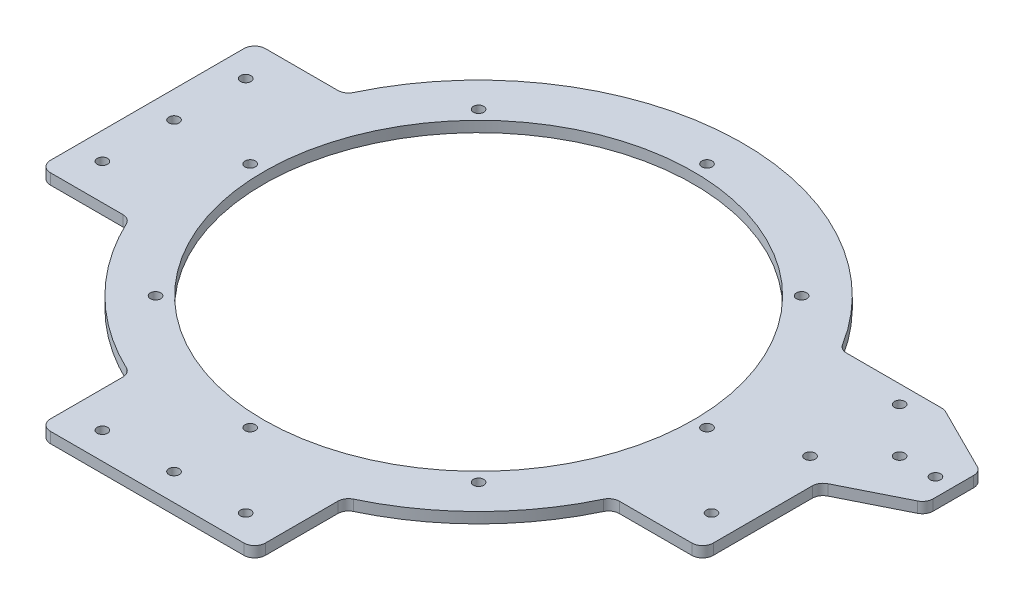
SolidWorks part; units mm, degrees
material "Thornel Mat VMA"
ref_plane "前视基准面" through (0, 0, 0) normal (0, 0, 1) x (1, 0, 0)
ref_plane "上视基准面" through (0, 0, 0) normal (0, 1, 0) x (1, 0, 0)
ref_plane "右视基准面" through (0, 0, 0) normal (1, 0, 0) x (0, 0, -1)
other "Configuration Table"
sketch "草图1" plane through (0, 0, 0) normal (0, 1, 0) x (1, 0, 0)
  line L0 (-94.2968, 0) -> (104.7583, 0) construction
  line L1 (0, 85) -> (0, -117.5844) construction
  line L2 (-45.0781, 45.0781) -> (0, 0) construction
  line L3 (-41.1681, -85) -> (39.8954, -85) construction
  line L4 (-42.9076, 77.5) -> (64.6874, 77.5) construction
  line L5 (-85, 28.1793) -> (-85, -30) construction
  line L6 (85, 63.75) -> (85, -19.3516) construction
  line L12 (-30, -92.5) -> (30, -92.5)
  line L15 (92.5, -30) -> (92.5, 30) construction
  line L18 (30, 85) -> (-30, 85) construction
  line L19 (-92.5, 30) -> (-92.5, -30)
  line L20 (-30, -92.5) -> (-30, -67.3726)
  line L21 (30, -92.5) -> (30, -67.3726)
  line L22 (-92.5, -30) -> (-67.3726, -30)
  line L23 (-92.5, 30) -> (-67.3726, 30)
  line L24 (92.5, 30) -> (67.3726, 30) construction
  line L25 (92.5, -30) -> (67.3726, -30)
  line L26 (-30, 85) -> (-30, 67.3726) construction
  line L27 (30, 85) -> (30, 67.3726) construction
  line L28 (65.6866, 20) -> (127.8038, 20) construction
  line L29 (92.5, 30) -> (92.5, 37.5) construction
  line L30 (92.5, 37.5) -> (63.5044, 37.5)
  line L31 (92.5, 37.5) -> (112.5, 27.5)
  line L32 (112.5, 27.5) -> (112.5, 12.5)
  line L33 (112.5, 12.5) -> (92.5, 2.5)
  line L34 (92.5, 2.5) -> (92.5, -30)
  circle A0 centre (0, 0) radius 60
  circle A1 centre (0, 0) radius 63.75 construction
  circle A2 centre (0, 63.75) radius 1.45
  circle A3 centre (63.75, 0) radius 1.45
  circle A4 centre (-63.75, 0) radius 1.45
  circle A5 centre (0, -63.75) radius 1.45
  circle A6 centre (-45.0781, 45.0781) radius 1.45
  circle A7 centre (45.0781, 45.0781) radius 1.45
  circle A8 centre (45.0781, -45.0781) radius 1.45
  circle A9 centre (-45.0781, -45.0781) radius 1.45
  circle A11 centre (20, -85) radius 1.45
  circle A12 centre (-20, -85) radius 1.45
  circle A15 centre (20, 77.5) radius 2.1 construction
  circle A16 centre (-20, 77.5) radius 2.1 construction
  circle A18 centre (0, 77.5) radius 2.1 construction
  circle A19 centre (0, -85) radius 1.45
  circle A20 centre (-85, 0) radius 1.45
  circle A21 centre (-85, 20) radius 1.45
  circle A24 centre (-85, -20) radius 1.45
  circle A25 centre (85, -20) radius 1.45
  circle A26 centre (0, 0) radius 73.75 construction
  arc A27 (-30, 67.3726) -> (-67.3726, 30) centre (0, 0) ccw
  arc A28 (67.3726, 30) -> (30, 67.3726) centre (0, 0) ccw construction
  arc A29 (30, -67.3726) -> (67.3726, -30) centre (0, 0) ccw
  arc A30 (-30, -67.3726) -> (-67.3726, -30) centre (0, 0) cw
  arc A31 (-30, 67.3726) -> (30, 67.3726) centre (0, 0) cw
  arc A32 (30, 67.3726) -> (63.5044, 37.5) centre (0, 0) cw
  circle A33 centre (85, 32.5) radius 1.45
  circle A34 centre (97.5, 20) radius 1.45
  circle A35 centre (107.5, 20) radius 1.45
  circle A36 centre (85, 7.5) radius 1.45
  dimension "D1" = 120
  dimension "D2" = 127.5
  dimension "D4" = 2.9
  dimension "D6" = 2.9
  dimension "D8" = 20
  dimension "D10" = 4.2
  dimension "D12" = 85
  dimension "D13" = 2.9
  dimension "D14" = 20
  dimension "D15" = 2.9
  dimension "D21" = 147.5
  dimension "D22" = 10
  dimension "D25" = 12.5
  dimension "D26" = 5
  dimension "D28" = 10
  dimension "D31" = 5
  dimension "D16" = 10
  dimension "D33" = 12.5
  dimension "D32" = 5
  dimension "D3" = 45
  dimension "D5" = 85
  dimension "D7" = 20
  dimension "D9" = 77.5
  dimension "D11" = 85
  dimension "D17" = 7.5
  dimension "D18" = 7.5
  dimension "D19" = 7.5
  dimension "D20" = 7.5
  dimension "D23" = 10
  dimension "D24" = 10
  dimension "D27" = 5
  dimension "D29" = 7.5
  dimension "D30" = 7.5
extrude "凸台-拉伸1" add sketch "草图1" along normal blind 3
fillet "圆角2" radius 3 15 edges at (67.3726, 1.5, 30) (30, 1.5, 67.3726) (30, 1.5, 92.5) (-30, 1.5, 92.5) (-92.5, 1.5, 30) (-92.5, 1.5, -30) (-67.3726, 1.5, -30) (-30, 1.5, 67.3726) (-67.3726, 1.5, 30) (92.5, 1.5, -2.5) (92.5, 1.5, 30) (112.5, 1.5, -12.5) (112.5, 1.5, -27.5) (63.5044, 1.5, -37.5) (92.5, 1.5, -37.5)
